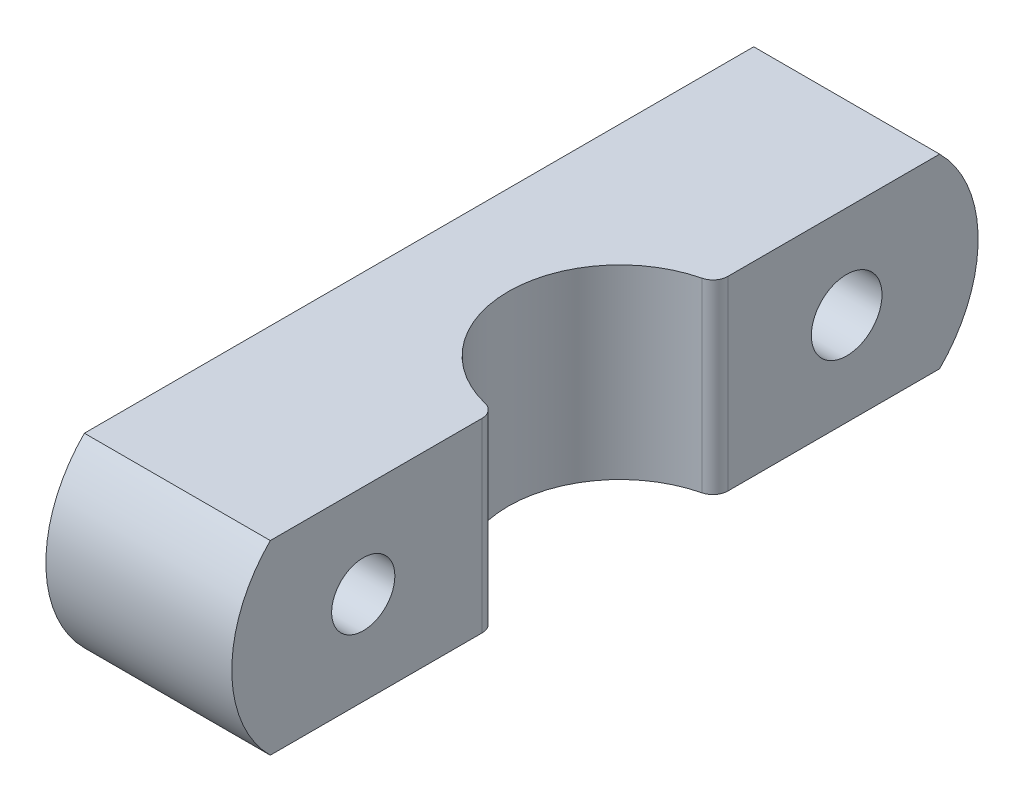
SolidWorks part; units mm, degrees
ref_plane "前视基准面" through (0, 0, 0) normal (0, 0, 1) x (1, 0, 0)
ref_plane "上视基准面" through (0, 0, 0) normal (0, 1, 0) x (1, 0, 0)
ref_plane "右视基准面" through (0, 0, 0) normal (1, 0, 0) x (0, 0, -1)
sketch "草图1" plane through (0, 0, 0) normal (1, 0, 0) x (0, 0, -1)
  line L0 (-10.6359, 16.4118) -> (2.9641, 16.4118)
  line L1 (-10.6359, 6.4118) -> (2.9641, 6.4118)
  line L2 (-10.6359, 16.4118) -> (-21.8359, 16.4118)
  line L3 (-21.8359, 6.4118) -> (-10.6359, 6.4118)
  line L4 (2.9641, 6.4118) -> (14.1641, 6.4118)
  line L5 (14.1641, 16.4118) -> (2.9641, 16.4118)
  arc A0 (-21.8359, 16.4118) -> (-21.8359, 6.4118) centre (-16.8359, 11.4118) ccw
  arc A1 (14.1641, 6.4118) -> (14.1641, 16.4118) centre (9.1641, 11.4118) ccw
  point P10 (0, 0)
extrude "凸台-拉伸1" add sketch "草图1" along normal blind 10 contours L0 L5 A1 L4 L1 L3 A0 L2
sketch "草图2" plane through (0, 6.4118, 0) normal (0, -1, 0) x (1, 0, 0)
  line L0 (10, 21.8359) -> (10, -14.1641) construction
  line L1 (10, 9.7823) -> (10, -2.1105)
  arc A2 (10, 9.7823) -> (10, -2.1105) centre (10.8, 3.8359) ccw
extrude "切除-拉伸1" cut sketch "草图2" against normal through all
fillet "圆角1" radius 0.8 2 edges at (10, 11.4118, -2.1105) (10, 11.4118, 9.7823)
sketch "草图3" plane through (10, 0, 0) normal (1, 0, 0) x (0, 0, -1)
  circle A0 centre (-16.8359, 11.4118) radius 1.7 construction
  circle A1 centre (9.1641, 11.4118) radius 1.9 construction
  circle A2 centre (-16.8359, 11.4118) radius 1.7
  circle A3 centre (9.1641, 11.4118) radius 1.9
extrude "切除-拉伸2" cut sketch "草图3" against normal blind 10
